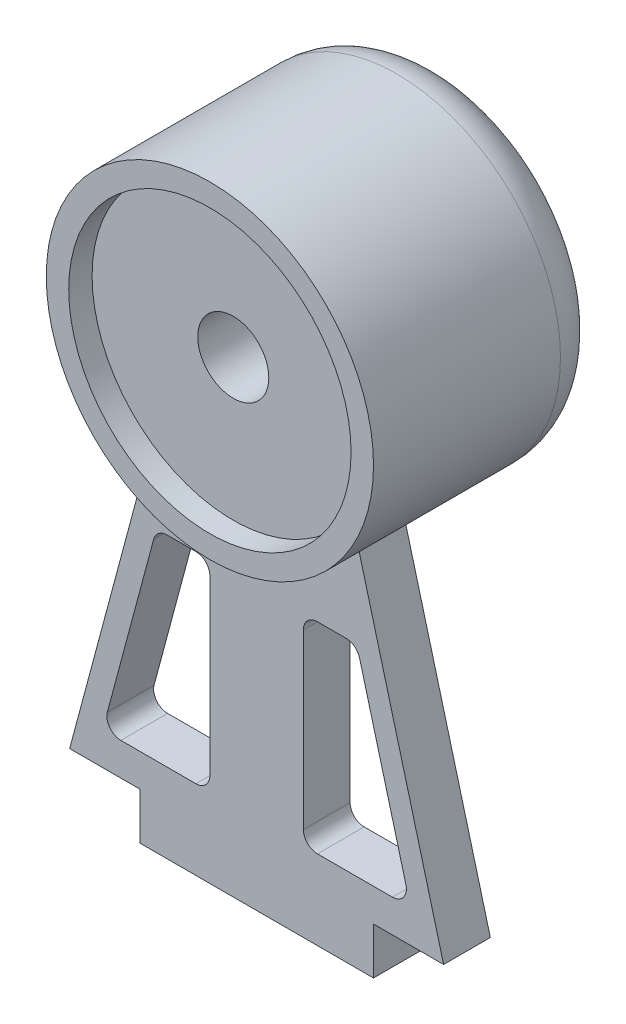
SolidWorks part; units mm, degrees
other "Markup1"
sketch "Sketch7"
material "6061 Alloy"
ref_plane "Front Plane" through (0, 0, 0) normal (0, 0, 1) x (1, 0, 0)
ref_plane "Top Plane" through (0, 0, 0) normal (0, 1, 0) x (1, 0, 0)
ref_plane "Right Plane" through (0, 0, 0) normal (1, 0, 0) x (0, 0, -1)
sketch "Sketch2" plane through (0, 0, 0) normal (0, 0, 1) x (1, 0, 0)
  line L0 (-9.236, 0) -> (9.236, 0)
  line L1 (9.236, 0) -> (25.4, -60.325)
  line L2 (25.4, -60.325) -> (15.875, -60.325)
  line L3 (15.875, -60.325) -> (15.875, -66.675)
  line L4 (15.875, -66.675) -> (-15.875, -66.675)
  line L5 (0, -66.675) -> (0, 0) construction
  line L6 (-15.875, -60.325) -> (-15.875, -66.675)
  line L7 (-25.4, -60.325) -> (-15.875, -60.325)
  line L8 (-9.236, 0) -> (-25.4, -60.325)
  dimension "D1" = 15.875
  dimension "D2" = 6.35
  dimension "D3" = 66.675
  dimension "D4" = 75
  dimension "D5" = 9.525
extrude "Boss-Extrude1" add sketch "Sketch2" along normal mid plane 6.35
sketch "Sketch3" plane through (0, 0, 0) normal (1, 0, 0) x (0, 0, -1)
  line L0 (-9.525, 22.225) -> (-9.525, 0) construction
  line L2 (22.225, 0) -> (22.225, 15.875)
  line L3 (15.875, 22.225) -> (-9.525, 22.225)
  line L4 (-3.175, -60.325) -> (-3.175, 0) construction
  line L5 (-9.525, 22.225) -> (-9.525, 0)
  line L6 (-9.525, 0) -> (0, 0)
  line L7 (0, 0) -> (22.225, 0)
  arc A0 (22.225, 15.875) -> (15.875, 22.225) centre (15.875, 15.875) ccw
  point P4 (22.225, 22.225)
  dimension "D4" = 6.35
  dimension "D1" = 22.225
  dimension "D2" = 31.75
  dimension "D3" = 6.35
revolve "Revolve1" add sketch "Sketch3" angle 360 about L7
sketch "Sketch5" plane through (0, 0, 0) normal (1, 0, 0) x (0, 0, -1)
  line L0 (-9.525, 19.177) -> (-6.35, 19.177)
  line L1 (-9.525, 22.225) -> (-9.525, -22.225) construction
  line L2 (-6.35, 19.177) -> (-6.35, 4.826)
  line L3 (-6.35, 4.826) -> (12.954, 4.826)
  line L4 (12.954, 4.826) -> (12.954, 0)
  line L6 (-9.525, 0) -> (-9.525, 19.177)
  line L7 (-9.525, 0) -> (12.954, 0)
  point P8 (-7.9375, 19.177)
  dimension "D1" = 4.826
  dimension "D2" = 22.479
  dimension "D3" = 3.175
  dimension "D4" = 19.177
revolve "Cut-Revolve1" cut sketch "Sketch5" angle 360 about L7
sketch "Sketch6" plane through (0, 0, -3.175) normal (0, 0, -1) x (-1, 0, 0)
  line L0 (-13.9839, -29.9869) -> (-20.2794, -53.4819)
  line L1 (-18.4393, -55.88) -> (-8.255, -55.88)
  line L2 (-6.35, -53.975) -> (-6.35, -30.48)
  line L3 (-8.255, -28.575) -> (-12.1439, -28.575)
  line L4 (-15.875, -66.675) -> (-15.875, -60.325) construction
  line L5 (-25.4, -60.325) -> (-13.8858, -17.3533) construction
  line L6 (-15.875, -60.325) -> (-25.4, -60.325) construction
  line L7 (15.875, -66.675) -> (-15.875, -66.675) construction
  line L8 (0, 0) -> (0, -66.675) construction
  line L9 (8.255, -28.575) -> (12.1439, -28.575)
  line L10 (6.35, -53.975) -> (6.35, -30.48)
  line L11 (18.4393, -55.88) -> (8.255, -55.88)
  line L12 (13.9839, -29.9869) -> (20.2794, -53.4819)
  arc A0 (-8.255, -55.88) -> (-6.35, -53.975) centre (-8.255, -53.975) ccw
  arc A1 (-20.2794, -53.4819) -> (-18.4393, -55.88) centre (-18.4393, -53.975) ccw
  arc A2 (-6.35, -30.48) -> (-8.255, -28.575) centre (-8.255, -30.48) ccw
  arc A3 (-13.9839, -29.9869) -> (-12.1439, -28.575) centre (-12.1439, -30.48) cw
  arc A4 (13.9839, -29.9869) -> (12.1439, -28.575) centre (12.1439, -30.48) ccw
  arc A5 (6.35, -30.48) -> (8.255, -28.575) centre (8.255, -30.48) cw
  arc A6 (20.2794, -53.4819) -> (18.4393, -55.88) centre (18.4393, -53.975) cw
  arc A7 (8.255, -55.88) -> (6.35, -53.975) centre (8.255, -53.975) cw
  dimension "D4" = 1.905
  dimension "D1" = 6.35
  dimension "D2" = 10.795
  dimension "1.5" = 38.1
  dimension "D3" = 3.175
extrude "Cut-Extrude1" cut sketch "Sketch6" against normal blind 6.35
